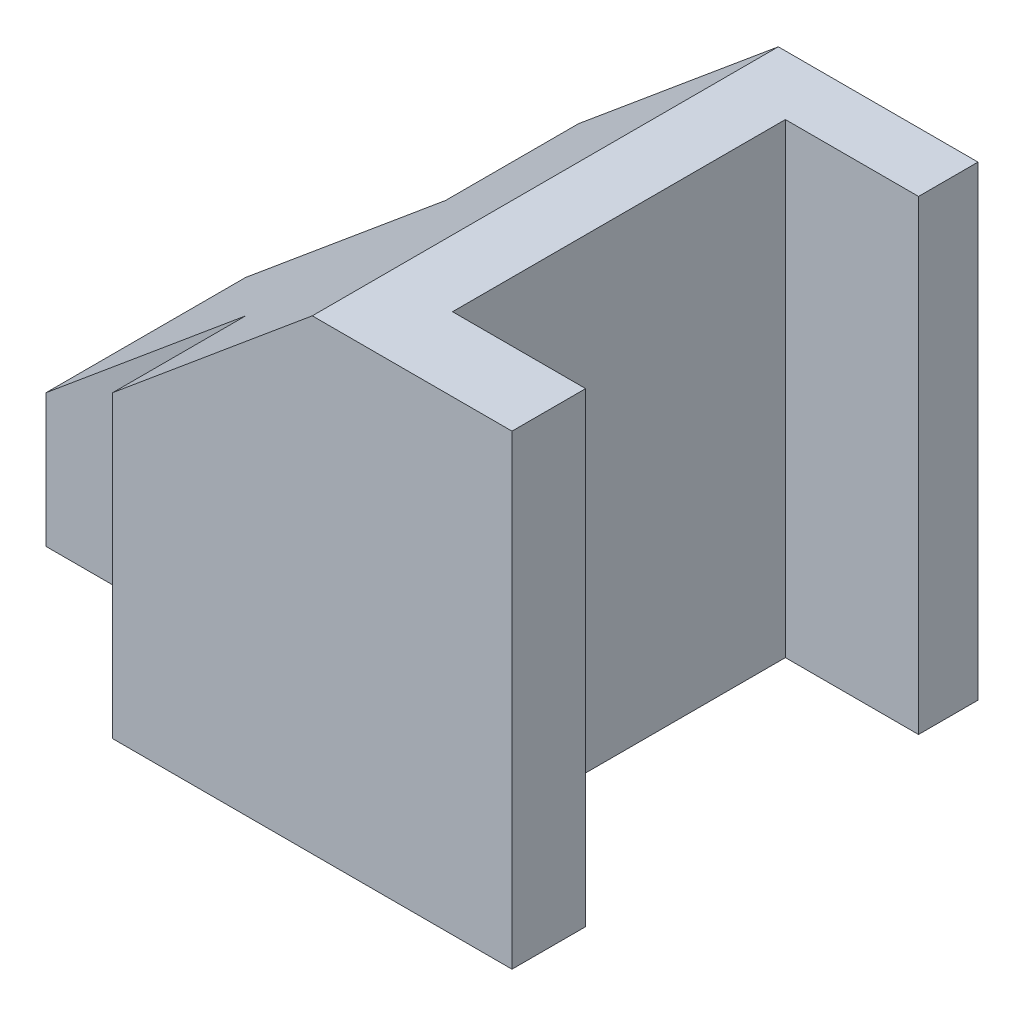
SolidWorks part; units mm, degrees
ref_plane "Front Plane" through (0, 0, 0) normal (0, 0, 1) x (1, 0, 0)
ref_plane "Top Plane" through (0, 0, 0) normal (0, 1, 0) x (1, 0, 0)
ref_plane "Right Plane" through (0, 0, 0) normal (1, 0, 0) x (0, 0, -1)
sketch "Sketch1" plane through (0, 0, 0) normal (0, 0, 1) x (1, 0, 0)
  line L0 (0, 0) -> (45000, 0)
  line L1 (45000, 0) -> (45000, 35000)
  line L2 (45000, 35000) -> (30000, 35000)
  line L3 (30000, 35000) -> (0, 10000)
  line L4 (0, 10000) -> (0, 0)
  dimension "D1" = 10000
  dimension "D2" = 45000
  dimension "D3" = 35000
  dimension "D4" = 15000
extrude "Boss-Extrude1" add sketch "Sketch1" along normal blind 35000
sketch "Sketch3" plane through (0, 35000, 0) normal (0, 1, 0) x (1, 0, 0)
  line L0 (45000, -35000) -> (45000, 0) construction
  line L1 (45000, -4467.0153) -> (35000, -4467.0153)
  line L2 (45000, -4467.0153) -> (45000, -29467.0153)
  line L3 (45000, -29467.0153) -> (35000, -29467.0153)
  line L4 (35000, -4467.0153) -> (35000, -29467.0153)
  line L5 (32980.9153, -16967.0153) -> (48624.0726, -16967.0153) construction
  dimension "D1" = 12500
  dimension "D2" = 25000
  dimension "D3" = 10000
extrude "Cut-Extrude4" cut sketch "Sketch3" against normal through all
sketch "Sketch4" plane through (0, 0, 35000) normal (0, 0, 1) x (1, 0, 0)
  line L0 (0, 0) -> (15000, 0)
  line L1 (0, 0) -> (45000, 0) construction
  line L2 (15000, 0) -> (15000, 22500)
  line L3 (30000, 35000) -> (0, 10000) construction
  line L4 (15000, 22500) -> (0, 10000)
  line L5 (0, 10000) -> (0, 0)
  dimension "D1" = 15000
extrude "Cut-Extrude5" cut sketch "Sketch4" against normal blind 10000
sketch "Sketch5" plane through (0, 0, 0) normal (0, 0, -1) x (-1, 0, 0)
  line L0 (0, 0) -> (0, 10000)
  line L1 (0, 10000) -> (-15000, 22500)
  line L2 (-30000, 35000) -> (0, 10000) construction
  line L3 (-15000, 22500) -> (-15000, 0)
  line L4 (0, 0) -> (-45000, 0) construction
  line L5 (-15000, 0) -> (0, 0)
  dimension "D1" = 15000
extrude "Cut-Extrude6" cut sketch "Sketch5" against normal blind 10000
